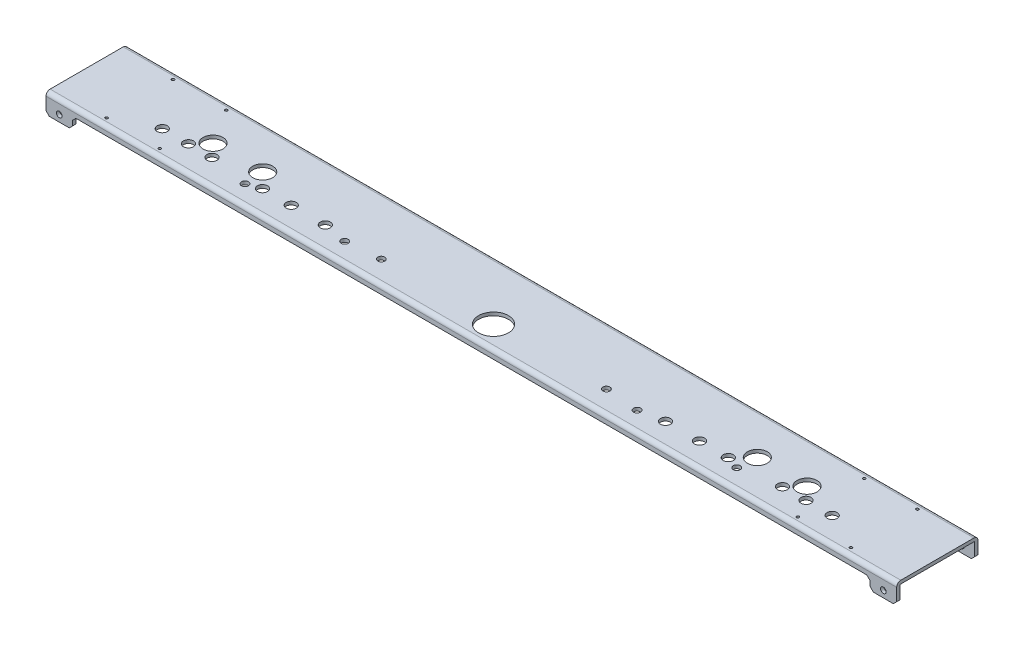
SolidWorks part; units mm, degrees
ref_plane "Front Plane" through (0, 0, 0) normal (0, 0, 1) x (1, 0, 0)
ref_plane "Top Plane" through (0, 0, 0) normal (0, 1, 0) x (1, 0, 0)
ref_plane "Right Plane" through (0, 0, 0) normal (1, 0, 0) x (0, 0, -1)
ref_plane "Plane1" through (0, -15.875, 0) normal (0, -1, 0) x (1, 0, 0)
sketch "Sketch1" plane through (0, -15.875, 0) normal (0, -1, 0) x (1, 0, 0)
  line L0 (812.8, 3.937) -> (0, 3.937)
  line L1 (0, 3.937) -> (0, -73.787)
  line L2 (0, -73.787) -> (812.8, -73.787)
  line L3 (812.8, -73.787) -> (812.8, 3.937)
extrude "Boss-Extrude1" add sketch "Sketch1" against normal blind 19.05
sketch "Sketch2" plane through (0, 0, 0) normal (-1, 0, 0) x (0, 0, 1)
  line L0 (-70.612, -15.875) -> (0.762, -15.875)
  line L1 (0.762, -15.875) -> (0.762, 0)
  line L2 (0.762, 0) -> (-70.612, 0)
  line L3 (-70.612, 0) -> (-70.612, -15.875)
extrude "Cut-Extrude1" cut sketch "Sketch2" against normal through all
sketch "Sketch3" plane through (0, 0, 3.937) normal (0, 0, 1) x (1, 0, 0)
  line L0 (787.4, -15.875) -> (787.4, -4.7625)
  line L1 (787.4, -4.7625) -> (25.4, -4.7625)
  line L2 (25.4, -4.7625) -> (25.4, -15.875)
  line L3 (25.4, -15.875) -> (787.4, -15.875)
extrude "Cut-Extrude2" cut sketch "Sketch3" against normal up to next
hole_wizard "Hole1" positions "Sketch5" profile "Sketch4" legacy
sketch "Sketch5" plane through (0, 3.175, 0) normal (0, 1, 0) x (1, 0, 0)
  point P0 (406.4, 17.272)
sketch "Sketch4" plane through (406.4, 3.175, -17.272) normal (1, 0, 0) x (0, 0, 1)
  line L0 (0, 0) -> (0, 19.05)
  line L1 (0, 19.05) -> (14.2875, 19.05)
  line L2 (14.2875, 19.05) -> (14.2875, 0)
  line L3 (14.2875, 0) -> (0, 0)
  line L4 (0, 110) -> (0, -10) construction
  dimension "Diameter" = 28.575
  dimension "Depth" = 19.05
hole_wizard "Hole2" positions "Sketch7" profile "Sketch6" legacy
sketch "Sketch7" plane through (0, 3.175, 0) normal (0, 1, 0) x (1, 0, 0)
  point P0 (568.9249, 19.05)
  point P1 (601.4385, 19.05)
  point P2 (628.9477, 19.05)
  point P3 (243.8751, 19.05)
  point P4 (211.3615, 19.05)
  point P5 (183.8523, 19.05)
  point P6 (678.9442, 20.828)
  point P7 (701.4504, 20.828)
  point P8 (726.4609, 20.828)
  point P9 (133.8558, 20.828)
  point P10 (111.3496, 20.828)
  point P11 (86.3391, 20.828)
sketch "Sketch6" plane through (568.9249, 3.175, -19.05) normal (1, 0, 0) x (0, 0, 1)
  line L0 (0, 0) -> (0, 19.05)
  line L1 (0, 19.05) -> (4.826, 19.05)
  line L2 (4.826, 19.05) -> (4.826, 0)
  line L3 (4.826, 0) -> (0, 0)
  line L4 (0, 110) -> (0, -10) construction
  dimension "Diameter" = 9.652
  dimension "Depth" = 19.05
hole_wizard "#2 Clearance Hole1" positions "Sketch9" profile "Sketch8" hole size "#2" standard "ANSI Inch"
sketch "Sketch9" plane through (0, 3.175, 0) normal (0, 1, 0) x (1, 0, 0)
  point P0 (711.2, 3.175)
  point P1 (711.2, 66.675)
  point P2 (762, 3.175)
  point P3 (762, 66.675)
  point P4 (101.6, 3.175)
  point P5 (50.8, 3.175)
  point P6 (101.6, 66.675)
  point P7 (50.8, 66.675)
sketch "Sketch8" plane through (711.2, 3.175, -3.175) normal (1, 0, 0) x (0, 0, 1)
  line L0 (0, 0) -> (0, 19.05)
  line L1 (0, 19.05) -> (1.27, 19.05)
  line L2 (1.27, 19.05) -> (1.27, 0)
  line L5 (1.27, 0) -> (0, 0)
  line L11 (0, -6.35) -> (0, 107.95) construction
  dimension "Thru Hole Dia." = 2.54
  dimension "Thru Hole Depth" = 19.05
hole_wizard "3/4 (0.75) Diameter Hole1" positions "Sketch11" profile "Sketch10" hole size "3/4" standard "ANSI Inch"
sketch "Sketch11" plane through (0, 3.175, 0) normal (0, 1, 0) x (1, 0, 0)
  point P0 (690.1973, 33.02)
  point P1 (642.7129, 33.02)
  point P2 (170.0871, 33.02)
  point P3 (122.6027, 33.02)
sketch "Sketch10" plane through (690.1973, 3.175, -33.02) normal (1, 0, 0) x (0, 0, 1)
  line L0 (0, 0) -> (0, 19.05)
  line L1 (0, 19.05) -> (9.525, 19.05)
  line L2 (9.525, 19.05) -> (9.525, 0)
  line L5 (9.525, 0) -> (0, 0)
  line L11 (0, -6.35) -> (0, 107.95) construction
  dimension "Thru Hole Dia." = 19.05
  dimension "Thru Hole Depth" = 19.05
hole_wizard "1/4 Clearance Hole1" positions "Sketch13" profile "Sketch12" hole size "1/4" standard "ANSI Inch"
sketch "Sketch13" plane through (0, 3.175, 0) normal (0, 1, 0) x (1, 0, 0)
  point P0 (641.35, 14.732)
  point P1 (546.1, 14.732)
  point P2 (171.45, 14.732)
  point P3 (266.7, 14.732)
  point P4 (513.9255, 17.5473)
  point P5 (298.8745, 17.5473)
sketch "Sketch12" plane through (641.35, 3.175, -14.732) normal (1, 0, 0) x (0, 0, 1)
  line L0 (0, 0) -> (0, 19.05)
  line L1 (0, 19.05) -> (3.3528, 19.05)
  line L2 (3.3528, 19.05) -> (3.3528, 0)
  line L5 (3.3528, 0) -> (0, 0)
  line L11 (0, -6.35) -> (0, 107.95) construction
  dimension "Thru Hole Dia." = 6.7056
  dimension "Thru Hole Depth" = 19.05
hole_wizard "#10 Clearance Hole1" positions "Sketch15" profile "Sketch14" hole size "#10" standard "ANSI Inch"
sketch "Sketch15" plane through (0, 0, 0.762) normal (0, 0, -1) x (-1, 0, 0)
  point P0 (-12.7, -9.525)
  point P1 (-800.1, -9.525)
sketch "Sketch14" plane through (12.7, -9.525, 0.762) normal (1, 0, 0) x (0, 1, 0)
  line L0 (0, 0) -> (0, 3.175)
  line L1 (0, 3.175) -> (2.667, 3.175)
  line L2 (2.667, 3.175) -> (2.667, 0)
  line L5 (2.667, 0) -> (0, 0)
  line L11 (0, -6.35) -> (0, 107.95) construction
  dimension "Thru Hole Dia." = 5.334
  dimension "Thru Hole Depth" = 3.175
hole_wizard "#10 Clearance Hole2" positions "Sketch17" profile "Sketch16" hole size "#10" standard "ANSI Inch"
sketch "Sketch17" plane through (0, 0, -73.787) normal (0, 0, -1) x (-1, 0, 0)
  point P0 (-800.1, -9.525)
  point P1 (-774.7, -9.525)
  point P2 (-749.3, -9.525)
  point P3 (-723.9, -9.525)
  point P4 (-698.5, -9.525)
  point P5 (-673.1, -9.525)
  point P6 (-647.7, -9.525)
  point P7 (-622.3, -9.525)
  point P8 (-596.9, -9.525)
  point P9 (-571.5, -9.525)
  point P10 (-546.1, -9.525)
  point P11 (-520.7, -9.525)
  point P12 (-495.3, -9.525)
  point P13 (-469.9, -9.525)
  point P14 (-444.5, -9.525)
  point P15 (-419.1, -9.525)
  point P16 (-393.7, -9.525)
  point P17 (-368.3, -9.525)
  point P18 (-342.9, -9.525)
  point P19 (-317.5, -9.525)
  point P20 (-292.1, -9.525)
  point P21 (-266.7, -9.525)
  point P22 (-241.3, -9.525)
  point P23 (-215.9, -9.525)
  point P24 (-190.5, -9.525)
  point P25 (-165.1, -9.525)
  point P26 (-139.7, -9.525)
  point P27 (-114.3, -9.525)
  point P28 (-88.9, -9.525)
  point P29 (-63.5, -9.525)
  point P30 (-38.1, -9.525)
  point P31 (-12.7, -9.525)
sketch "Sketch16" plane through (800.1, -9.525, -73.787) normal (1, 0, 0) x (0, 1, 0)
  line L0 (0, 0) -> (0, 77.724)
  line L1 (0, 77.724) -> (2.667, 77.724)
  line L2 (2.667, 77.724) -> (2.667, 0)
  line L5 (2.667, 0) -> (0, 0)
  line L11 (0, -6.35) -> (0, 107.95) construction
  dimension "Thru Hole Dia." = 5.334
  dimension "Thru Hole Depth" = 77.724
chamfer "Chamfer1" distance 3.175 angle 45 8 edges at (25.4, -4.7625, 2.3495) (787.4, -4.7625, 2.3495) (0, -15.875, 2.3495) (25.4, -15.875, 2.3495) (812.8, -15.875, -72.1995) (812.8, -15.875, 2.3495) (0, -15.875, -72.1995) (787.4, -15.875, 2.3495)
fillet "Fillet1" radius 0.762 2 edges at (406.4, 0, -70.612) (406.4, 0, 0.762)
fillet "Fillet2" radius 3.937 2 edges at (406.4, 3.175, 3.937) (406.4, 3.175, -73.787)
